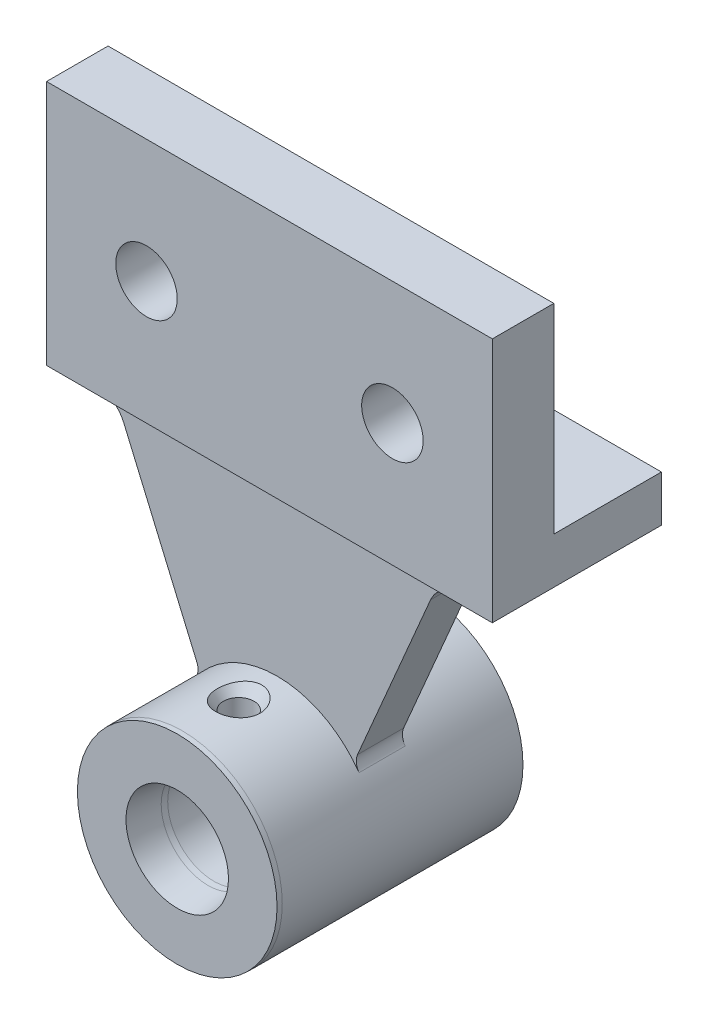
SolidWorks part; units mm, degrees
ref_plane "前视基准面" through (0, 0, 0) normal (0, 0, 1) x (1, 0, 0)
ref_plane "上视基准面" through (0, 0, 0) normal (0, 1, 0) x (1, 0, 0)
ref_plane "右视基准面" through (0, 0, 0) normal (1, 0, 0) x (0, 0, -1)
other "Configuration Table"
sketch "草图1" plane through (0, 0, 0) normal (0, 0, 1) x (1, 0, 0)
  line L1 (-43.5, 24) -> (43.5, 24)
  line L2 (-43.5, 24) -> (-43.5, -24)
  line L3 (-43.5, -24) -> (43.5, -24)
  line L4 (43.5, 24) -> (43.5, -24)
  line L5 (-43.5, 24) -> (43.5, -24) construction
  line L6 (-43.5, -24) -> (43.5, 24) construction
  point P0 (0, 0)
  dimension "D1" = 87
  dimension "D2" = 48
extrude "凸台-拉伸1" add sketch "草图1" against normal blind 12
sketch "草图3" plane through (0, 0, -12) normal (0, 0, -1) x (-1, 0, 0)
  line L0 (43.5, -24) -> (-43.5, -24) construction
  line L1 (-37.5, 15) -> (37.5, 15)
  line L2 (-37.5, 15) -> (-37.5, -15)
  line L3 (-37.5, -15) -> (37.5, -15)
  line L4 (37.5, 15) -> (37.5, -15)
  line L5 (-37.5, 15) -> (37.5, -15) construction
  line L6 (-37.5, -15) -> (37.5, 15) construction
  point P0 (0, 0)
  dimension "D1" = 9
  dimension "D2" = 75
extrude "切除-拉伸1" cut sketch "草图3" against normal blind 3
sketch "草图4" plane through (0, 0, 0) normal (0, 0, 1) x (1, 0, 0)
  line L0 (0, 25.8066) -> (0, -20.5248) construction
  circle A0 centre (24, 0) radius 6
  circle A1 centre (-24, 0) radius 6
  dimension "D2" = 12
  dimension "D3" = 12
  dimension "D1" = 48
extrude "切除-拉伸2" cut sketch "草图4" against normal through all
sketch "草图5" plane through (0, 0, -12) normal (0, 0, -1) x (-1, 0, 0)
  line L0 (-43.5, -24) -> (-43.5, 24) construction
  line L1 (-43.5, -15) -> (43.5, -15)
  line L2 (-43.5, -15) -> (-43.5, -24)
  line L3 (-43.5, -24) -> (43.5, -24)
  line L4 (43.5, -15) -> (43.5, -24)
extrude "凸台-拉伸2" add sketch "草图5" along normal blind 21
ref_plane "基准面1" through (0, 0, -6) normal (0, 0, 1) x (1, 0, 0)
sketch "草图7" plane through (0, 0, -6) normal (0, 0, 1) x (1, 0, 0)
  circle A0 centre (0, -75) radius 19.5
  point P2 (43.5, -15)
  dimension "D1" = 39
  dimension "D2" = 60
extrude "凸台-拉伸3" add sketch "草图7" along normal mid plane 48 separate body
sketch "草图8" plane through (0, 0, -6) normal (0, 0, 1) x (1, 0, 0)
  circle A0 centre (0, -75) radius 9
  dimension "D1" = 18
extrude "切除-拉伸3" cut sketch "草图8" against normal mid plane 34
ref_plane "基准面2" through (0, -75, 0) normal (0, 1, 0) x (1, 0, 0)
sketch "草图10" plane through (0, -75, 0) normal (0, 1, 0) x (1, 0, 0)
  line L0 (0, -18) -> (0, -11)
  line L1 (-19.5, -18) -> (19.5, -18) construction
  line L2 (0, -11) -> (9, -11)
  line L3 (9, -11) -> (10, -18)
  line L4 (10, -18) -> (0, -18)
  dimension "D1" = 9
  dimension "D2" = 10
  dimension "D3" = 7
revolve "切除-旋转1" cut sketch "草图10" angle 360 about L0
mirror "镜向1" about plane through (0, 0, -6) normal (0, 0, 1) of "切除-旋转1"
sketch "草图12" plane through (0, 0, -6) normal (0, 0, 1) x (1, 0, 0)
  line L0 (-29.9422, -27.6386) -> (-15.6874, -60.9344)
  line L2 (0, 24) -> (0, -102.9568) construction
  line L3 (43.5, 24) -> (-43.5, 24) construction
  line L4 (29.9422, -27.6386) -> (15.6874, -60.9344)
  line L5 (-35.458, -24) -> (35.458, -24)
  circle A0 centre (0, -75) radius 19.5 construction
  arc A1 (15.9859, -63.8331) -> (-15.9859, -63.8331) centre (0, -75) ccw
  arc A2 (-29.9422, -27.6386) -> (-35.458, -24) centre (-35.458, -30) ccw
  arc A3 (29.9422, -27.6386) -> (35.458, -24) centre (35.458, -30) cw
  arc A4 (-15.9859, -63.8331) -> (-15.6874, -60.9344) centre (-18.4453, -62.1151) ccw
  arc A5 (15.9859, -63.8331) -> (15.6874, -60.9344) centre (18.4453, -62.1151) cw
  dimension "D1" = 6
  dimension "D3" = 6
  dimension "D4" = 6
extrude "凸台-拉伸4" add sketch "草图12" along normal mid plane 9
ref_plane "基准面3" through (0, -55.5, 0) normal (0, 1, 0) x (1, 0, 0)
sketch "草图13" plane through (0, -55.5, 0) normal (0, 1, 0) x (1, 0, 0)
  line L0 (-19.5, -18) -> (19.5, -18) construction
  circle A0 centre (0, -6) radius 3
  dimension "D1" = 6
  dimension "D2" = 12
extrude "切除-拉伸4" cut sketch "草图13" against normal up to surface (10.7857 mm away)
ref_plane "基准面4" through (0, 0, 6) normal (0, 0, 1) x (1, 0, 0)
sketch "草图14" plane through (0, 0, 6) normal (0, 0, 1) x (1, 0, 0)
  line L0 (0, -55.5) -> (0, -57.5)
  line L1 (13.2, -55.5) -> (-13.2, -55.5) construction
  line L2 (0, -57.5) -> (3, -57.5)
  line L3 (3, -57.5) -> (4.5, -55.5)
  line L4 (4.5, -55.5) -> (0, -55.5)
  dimension "D1" = 2
  dimension "D2" = 4.5
  dimension "D3" = 3
revolve "切除-旋转2" cut sketch "草图14" angle 360 about L0
chamfer "倒角6" distance 1 angle 1 4 edges at (19.5, -75, -30) (19.5, -75, 18) (9, -75, -23) (9, -75, 11)
